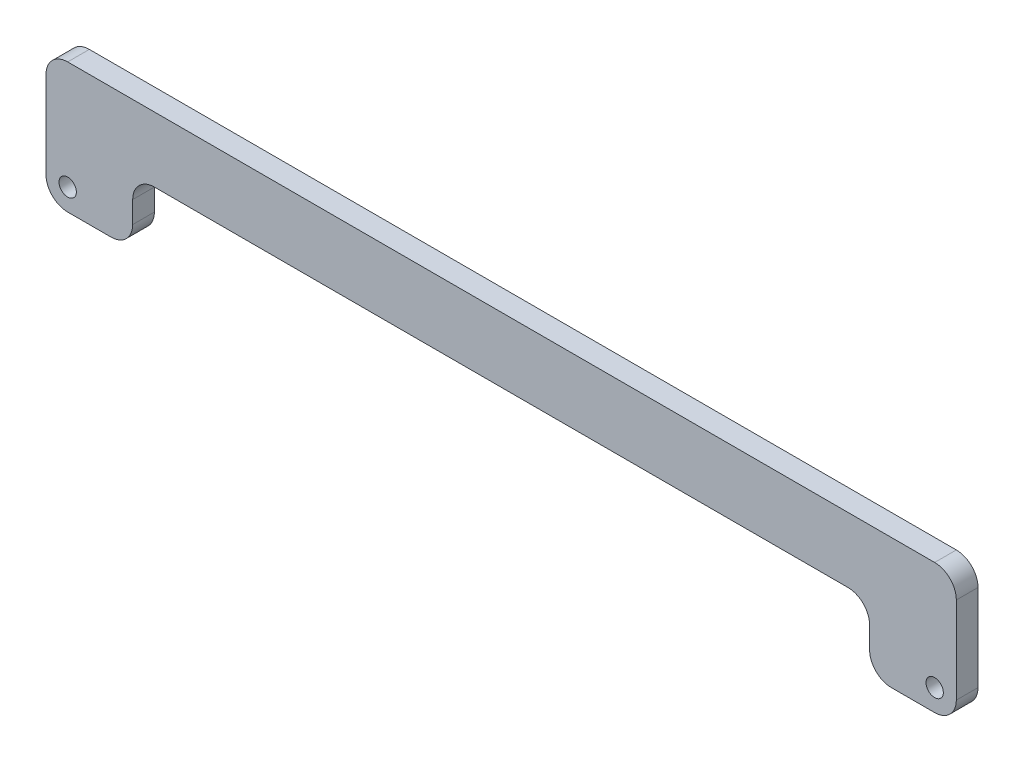
SolidWorks part; units mm, degrees
ref_plane "Plan de face" through (0, 0, 0) normal (0, 0, 1) x (1, 0, 0)
ref_plane "Plan de dessus" through (0, 0, 0) normal (0, 1, 0) x (1, 0, 0)
ref_plane "Plan de droite" through (0, 0, 0) normal (1, 0, 0) x (0, 0, -1)
sketch "Esquisse1" plane through (0, 0, 0) normal (0, 0, 1) x (1, 0, 0)
  line L0 (0, 5) -> (210, 5) construction
  line L1 (0, 0) -> (210, 0) construction
  line L2 (0, 0) -> (0, 30)
  line L3 (0, 30) -> (210, 30)
  line L4 (210, 0) -> (210, 30)
  line L5 (210, 0) -> (190, 0)
  line L6 (190, 0) -> (190, 15)
  line L7 (190, 15) -> (20, 15)
  line L8 (20, 15) -> (20, 0)
  line L9 (20, 0) -> (0, 0)
  circle A0 centre (5, 5) radius 2
  circle A1 centre (45, 5) radius 2 construction
  circle A2 centre (85, 5) radius 2 construction
  circle A3 centre (125, 5) radius 2 construction
  circle A4 centre (165, 5) radius 2 construction
  circle A5 centre (205, 5) radius 2
  dimension "D1" = 4
  dimension "D2" = 5
  dimension "D3" = 25
  dimension "D4" = 5
  dimension "D5" = 5
  dimension "D6" = 40
  dimension "D8" = 15
  dimension "D9" = 10
  dimension "D7" = 6
extrude "Boss.-Extru.1" add sketch "Esquisse1" along normal blind 5
fillet "Congé1" radius 5 8 edges at (210, 30, 2.5) (0, 30, 2.5) (0, 0, 2.5) (20, 0, 2.5) (20, 15, 2.5) (210, 0, 2.5) (190, 15, 2.5) (190, 0, 2.5)
